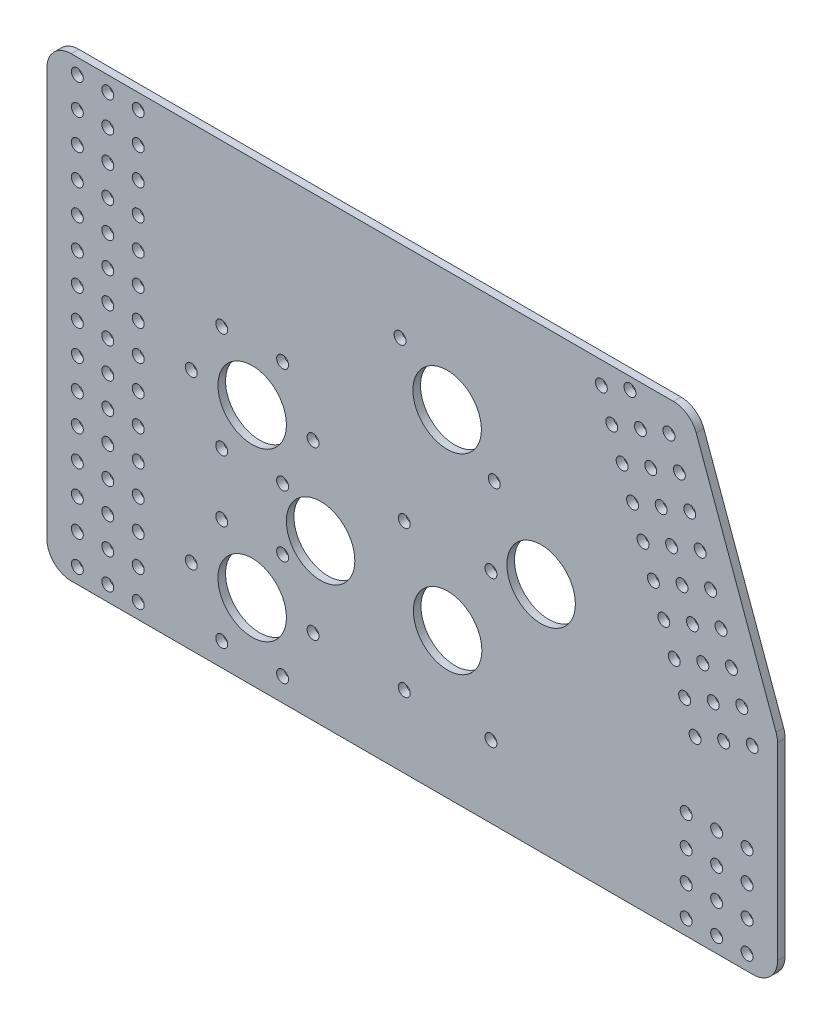
SolidWorks part; units mm, degrees
ref_plane "Front Plane" through (0, 0, 0) normal (0, 0, 1) x (1, 0, 0)
ref_plane "Top Plane" through (0, 0, 0) normal (0, 1, 0) x (1, 0, 0)
ref_plane "Right Plane" through (0, 0, 0) normal (1, 0, 0) x (0, 0, -1)
sketch "Sketch6" plane through (0, 0, 0) normal (0, 0, 1) x (1, 0, 0)
  line L0 (-62.0347, 275.0603) -> (206.4353, 275.0603)
  line L3 (206.4353, 275.0603) -> (242.7653, 175.2445)
  line L4 (242.7653, 175.2445) -> (242.7653, 84.5603)
  line L6 (242.7653, 84.5603) -> (-62.0347, 84.5603)
  line L7 (-62.0347, 84.5603) -> (-62.0347, 275.0603)
  line L8 (-49.3347, 268.7103) -> (-36.6347, 268.7103) construction
  line L9 (-49.3347, 268.7103) -> (-49.3347, 256.0103) construction
  line L10 (105.1393, -854.8604) -> (105.1393, 49145.1396) construction
  line L11 (169.2687, 265.7779) -> (173.6123, 253.8438) construction
  line L12 (204.6653, 129.0103) -> (204.6653, 116.3103) construction
  line L13 (23.6016, 116.2566) -> (23.6016, 141.6566) construction
  line L14 (23.6016, 185.8526) -> (23.6016, 211.2526) construction
  line L15 (-894.8607, 145.1396) -> (49105.1393, 145.1396) construction
  circle A0 centre (123.2241, 114.6088) radius 2.4892
  circle A1 centre (87.0545, 114.6088) radius 2.4892
  circle A2 centre (-49.3347, 268.7103) radius 2.4892
  circle A3 centre (-49.3347, 90.9103) radius 2.4892
  circle A4 centre (-36.6347, 268.7103) radius 2.4892
  circle A5 centre (-23.9347, 268.7103) radius 2.4892
  circle A6 centre (-36.6347, 256.0103) radius 2.4892
  circle A7 centre (-23.9347, 256.0103) radius 2.4892
  circle A8 centre (-36.6347, 243.3103) radius 2.4892
  circle A9 centre (-23.9347, 243.3103) radius 2.4892
  circle A10 centre (-36.6347, 230.6103) radius 2.4892
  circle A11 centre (-23.9347, 230.6103) radius 2.4892
  circle A12 centre (-36.6347, 217.9103) radius 2.4892
  circle A13 centre (-23.9347, 217.9103) radius 2.4892
  circle A14 centre (-36.6347, 205.2103) radius 2.4892
  circle A15 centre (-23.9347, 205.2103) radius 2.4892
  circle A16 centre (-36.6347, 192.5103) radius 2.4892
  circle A17 centre (-23.9347, 192.5103) radius 2.4892
  circle A18 centre (-36.6347, 179.8103) radius 2.4892
  circle A19 centre (-23.9347, 179.8103) radius 2.4892
  circle A20 centre (-36.6347, 167.1103) radius 2.4892
  circle A21 centre (-23.9347, 167.1103) radius 2.4892
  circle A22 centre (-36.6347, 154.4103) radius 2.4892
  circle A23 centre (-23.9347, 154.4103) radius 2.4892
  circle A24 centre (-36.6347, 141.7103) radius 2.4892
  circle A25 centre (-23.9347, 141.7103) radius 2.4892
  circle A26 centre (-36.6347, 129.0103) radius 2.4892
  circle A27 centre (-23.9347, 129.0103) radius 2.4892
  circle A28 centre (-36.6347, 116.3103) radius 2.4892
  circle A29 centre (-23.9347, 116.3103) radius 2.4892
  circle A30 centre (-36.6347, 103.6103) radius 2.4892
  circle A31 centre (-23.9347, 103.6103) radius 2.4892
  circle A32 centre (-36.6347, 90.9103) radius 2.4892
  circle A33 centre (-23.9347, 90.9103) radius 2.4892
  circle A34 centre (-49.3347, 256.0103) radius 2.4892
  circle A35 centre (-49.3347, 243.3103) radius 2.4892
  circle A36 centre (-49.3347, 230.6103) radius 2.4892
  circle A37 centre (-49.3347, 217.9103) radius 2.4892
  circle A38 centre (-49.3347, 205.2103) radius 2.4892
  circle A39 centre (-49.3347, 192.5103) radius 2.4892
  circle A40 centre (-49.3347, 179.8103) radius 2.4892
  circle A41 centre (-49.3347, 167.1103) radius 2.4892
  circle A42 centre (-49.3347, 154.4103) radius 2.4892
  circle A43 centre (-49.3347, 141.7103) radius 2.4892
  circle A44 centre (-49.3347, 129.0103) radius 2.4892
  circle A45 centre (-49.3347, 116.3103) radius 2.4892
  circle A46 centre (-49.3347, 103.6103) radius 2.4892
  circle A47 centre (-49.3347, 90.9103) radius 2.4892
  circle A48 centre (169.2687, 265.7779) radius 2.4892
  circle A49 centre (181.2028, 270.1215) radius 2.4892
  circle A50 centre (197.4805, 262.5311) radius 2.4892
  circle A51 centre (173.6123, 253.8438) radius 2.4892
  circle A52 centre (185.5464, 258.1874) radius 2.4892
  circle A53 centre (201.8242, 250.597) radius 2.4892
  circle A54 centre (177.956, 241.9097) radius 2.4892
  circle A55 centre (189.8901, 246.2533) radius 2.4892
  circle A56 centre (206.1678, 238.6629) radius 2.4892
  circle A57 centre (182.2996, 229.9756) radius 2.4892
  circle A58 centre (194.2337, 234.3192) radius 2.4892
  circle A59 centre (210.5115, 226.7288) radius 2.4892
  circle A60 centre (186.6433, 218.0415) radius 2.4892
  circle A61 centre (198.5774, 222.3851) radius 2.4892
  circle A62 centre (214.8551, 214.7947) radius 2.4892
  circle A63 centre (190.9869, 206.1074) radius 2.4892
  circle A64 centre (202.921, 210.451) radius 2.4892
  circle A65 centre (219.1988, 202.8606) radius 2.4892
  circle A66 centre (195.3306, 194.1733) radius 2.4892
  circle A67 centre (207.2647, 198.5169) radius 2.4892
  circle A68 centre (223.5424, 190.9265) radius 2.4892
  circle A69 centre (199.6743, 182.2392) radius 2.4892
  circle A70 centre (211.6083, 186.5828) radius 2.4892
  circle A71 centre (227.8861, 178.9924) radius 2.4892
  circle A72 centre (204.0179, 170.3051) radius 2.4892
  circle A73 centre (215.952, 174.6488) radius 2.4892
  circle A74 centre (232.2298, 167.0583) radius 2.4892
  circle A75 centre (208.3616, 158.371) radius 2.4892
  circle A76 centre (220.2957, 162.7147) radius 2.4892
  circle A78 centre (236.5734, 155.1242) radius 2.4892 [skipped]
  circle A79 centre (204.6653, 129.0103) radius 2.4892
  circle A80 centre (217.3653, 129.0103) radius 2.4892
  circle A81 centre (230.0653, 129.0103) radius 2.4892
  circle A82 centre (204.6653, 116.3103) radius 2.4892
  circle A83 centre (217.3653, 116.3103) radius 2.4892
  circle A84 centre (230.0653, 116.3103) radius 2.4892
  circle A85 centre (204.6653, 103.6103) radius 2.4892
  circle A86 centre (217.3653, 103.6103) radius 2.4892
  circle A87 centre (230.0653, 103.6103) radius 2.4892
  circle A88 centre (204.6653, 90.9103) radius 2.4892
  circle A89 centre (217.3653, 90.9103) radius 2.4892
  circle A90 centre (230.0653, 90.9103) radius 2.4892
  circle A91 centre (23.6016, 185.8526) radius 14.2875
  circle A92 centre (52.1422, 151.0564) radius 14.2875
  circle A93 centre (23.6016, 116.2566) radius 14.2875
  circle A94 centre (105.1393, 145.1396) radius 14.2875
  circle A95 centre (104.9447, 224.8273) radius 14.2875
  circle A96 centre (144.1424, 181.3926) radius 14.2875
  circle A99 centre (85.284, 241.0108) radius 2.4892
  circle A100 centre (23.6016, 141.6566) radius 2.4892
  circle A101 centre (45.5987, 128.9566) radius 2.4892
  circle A102 centre (45.5987, 103.5566) radius 2.4892
  circle A103 centre (23.6016, 90.8566) radius 2.4892
  circle A104 centre (1.6046, 103.5566) radius 2.4892
  circle A105 centre (1.6046, 128.9566) radius 2.4892
  circle A106 centre (23.6016, 211.2526) radius 2.4892
  circle A107 centre (45.5987, 198.5526) radius 2.4892
  circle A108 centre (45.5987, 173.1526) radius 2.4892
  circle A109 centre (23.6016, 160.4526) radius 2.4892
  circle A110 centre (1.6046, 173.1526) radius 2.4892
  circle A111 centre (1.6046, 198.5526) radius 2.4892
  circle A112 centre (123.2241, 175.6704) radius 2.4892
  circle A113 centre (87.0545, 175.6704) radius 2.4892
  circle A116 centre (124.6065, 208.849) radius 2.4892
  dimension "D1" = 4.9784
  dimension "D2" = 6.35
  dimension "D3" = 4.9784
  dimension "D10" = 4.9784
  dimension "D11" = 4.9784
  dimension "D12" = 4.9784
  dimension "D15" = 4.9784
  dimension "D16" = 4.9784
  dimension "D17" = 4.9784
  dimension "D20" = 4.9784
  dimension "D21" = 28.575
  dimension "D22" = 28.575
  dimension "D23" = 28.575
  dimension "D24" = 28.575
  dimension "D25" = 28.575
  dimension "D26" = 28.575
  dimension "D28" = 4.9784
  dimension "D32" = 4.9784
  dimension "D35" = 4.9784
  dimension "D38" = 4.9784
  dimension "D4" = 12.7
  dimension "D5" = 3
  dimension "D7" = 12.7
  dimension "D8" = 12.7
  dimension "D9" = 6.35
  dimension "D14" = 12.7
  dimension "D19" = 12.7
  dimension "D29" = 25.4
  dimension "D31" = 25.4
  dimension "D33" = 6
  dimension "D34" = 25.4
  dimension "D36" = 18.0848
  dimension "D37" = 30.5308
  dimension "D39" = 19.6607
  dimension "D40" = 16.1835
  dimension "D42" = 15.9782
  dimension "D43" = 19.6618
  dimension "D6" = 15
  dimension "D13" = 10
  dimension "D18" = 4
  dimension "D30" = 6
extrude "Boss-Extrude1" add sketch "Sketch6" along normal blind 3.175
fillet "Fillet1" radius 10.16 5 edges at (242.7653, 84.5603, 1.5875) (242.7653, 175.2445, 1.5875) (206.4353, 275.0603, 1.5875) (-62.0347, 84.5603, 1.5875) (-62.0347, 275.0603, 1.5875)
sketch "Sketch7" plane through (0, 0, 3.175) normal (0, 0, 1) x (1, 0, 0)
  line L0 (23.6016, 185.8526) -> (49.0016, 185.8526) construction
  line L1 (23.6016, 116.2566) -> (-1.7984, 116.2566) construction
  circle A0 centre (23.6016, 185.8526) radius 14.2875
  circle A1 centre (49.0016, 185.8526) radius 2.4892
  circle A2 centre (36.3016, 163.8555) radius 2.4892
  circle A3 centre (10.9016, 163.8555) radius 2.4892
  circle A4 centre (-1.7984, 185.8526) radius 2.4892
  circle A5 centre (10.9016, 207.8496) radius 2.4892
  circle A6 centre (36.3016, 207.8496) radius 2.4892
  circle A7 centre (23.6016, 116.2566) radius 14.2875
  circle A8 centre (-1.7984, 116.2566) radius 2.4892
  circle A9 centre (10.9016, 138.2536) radius 2.4892
  circle A10 centre (36.3016, 138.2536) radius 2.4892
  circle A11 centre (49.0016, 116.2566) radius 2.4892
  circle A12 centre (36.3016, 94.2595) radius 2.4892
  circle A13 centre (10.9016, 94.2595) radius 2.4892
  dimension "D1" = 28.575
  dimension "D2" = 4.9784
  dimension "D6" = 28.575
  dimension "D7" = 4.9784
  dimension "D3" = 25.4
  dimension "D5" = 25.4
  dimension "D8" = 25.4
  dimension "D10" = 25.4
  dimension "D4" = 6
  dimension "D9" = 6
extrude "Cut-Extrude1" cut sketch "Sketch7" against normal blind 3.175
sketch "Sketch8" plane through (0, 0, 3.175) normal (0, 0, 1) x (1, 0, 0)
  line L0 (23.6016, 185.8526) -> (23.6016, 211.2526) construction
  circle A1 centre (23.6016, 211.2526) radius 2.4892
  circle A2 centre (45.5987, 198.5526) radius 2.4892
  circle A3 centre (45.5987, 173.1526) radius 2.4892
  circle A4 centre (23.6016, 160.4526) radius 2.4892
  circle A5 centre (1.6046, 173.1526) radius 2.4892
  circle A6 centre (1.6046, 198.5526) radius 2.4892
  dimension "D1" = 4.9784
  dimension "D3" = 6
extrude "Boss-Extrude3" add sketch "Sketch8" against normal blind 3.175
sketch "Sketch10" plane through (0, 0, 3.175) normal (0, 0, 1) x (1, 0, 0)
  circle A0 centre (23.6016, 141.6566) radius 2.4892
  circle A1 centre (45.5987, 128.9566) radius 2.4892
  circle A2 centre (45.5987, 103.5566) radius 2.4892
  circle A3 centre (23.6016, 90.8566) radius 2.4892
  circle A4 centre (1.6046, 103.5566) radius 2.4892
  circle A5 centre (1.6046, 128.9566) radius 2.4892
  dimension "D1" = 4.9784
  dimension "D2" = 4.9784
  dimension "D3" = 4.9784
  dimension "D4" = 4.9784
  dimension "D5" = 4.9784
  dimension "D6" = 4.9784
extrude "Boss-Extrude4" add sketch "Sketch10" against normal blind 3.175
